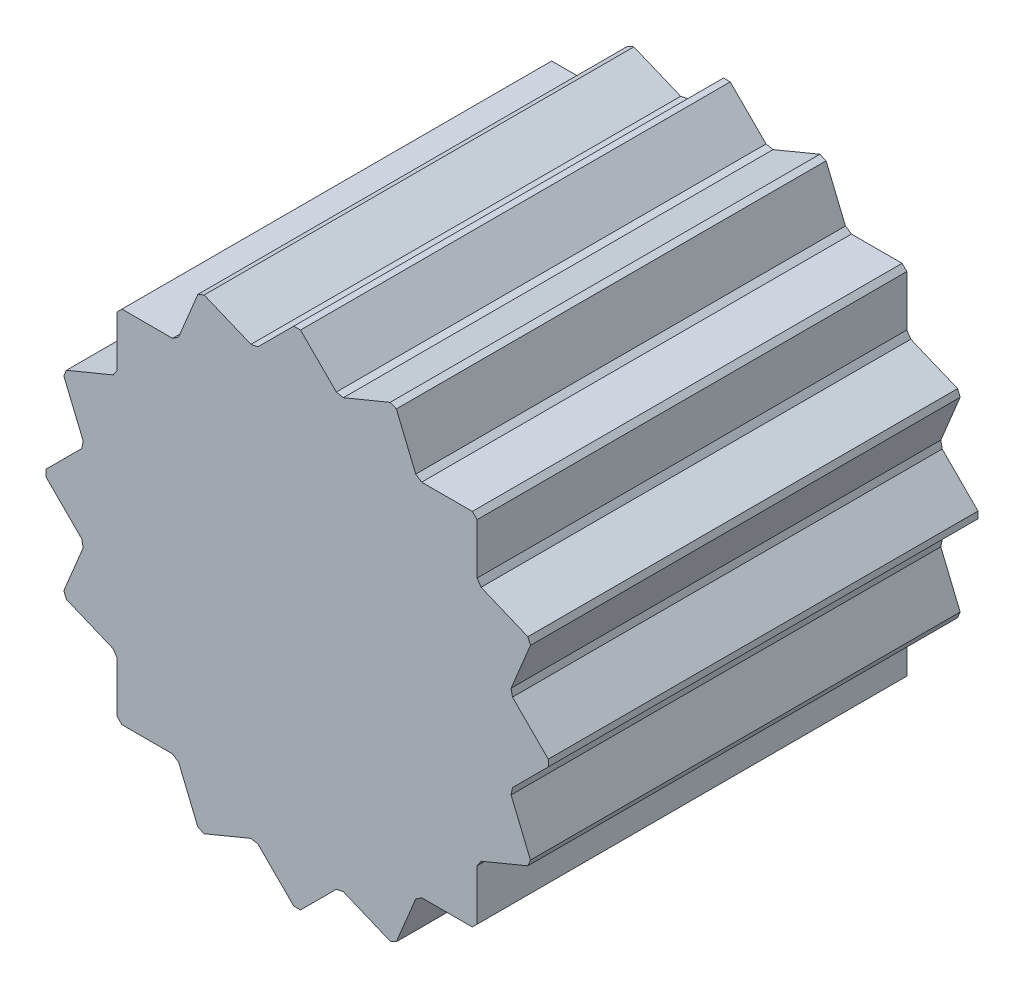
SolidWorks part; units mm, degrees
ref_plane "Front Plane" through (0, 0, 0) normal (0, 0, 1) x (1, 0, 0)
ref_plane "Top Plane" through (0, 0, 0) normal (0, 1, 0) x (1, 0, 0)
ref_plane "Right Plane" through (0, 0, 0) normal (1, 0, 0) x (0, 0, -1)
sketch "Sketch2" plane through (0, 0, 0) normal (0, 0, 1) x (1, 0, 0)
  circle A0 centre (0, 0) radius 15.2789
  dimension "D1" = 30.5577
extrude "Boss-Extrude1" add sketch "Sketch2" along normal blind 30
sketch "Sketch3" plane through (0, 0, 0) normal (0, 0, -1) x (-1, 0, 0)
  line L0 (-2.7352, 15.0321) -> (-0.2352, 17.5321)
  line L1 (-0.2352, 17.5321) -> (0.2352, 17.5321)
  line L2 (0.2352, 17.5321) -> (2.7352, 15.0321)
  line L3 (-2.7352, 15.0321) -> (2.7352, 15.0321) construction
  arc A0 (2.7352, 15.0321) -> (-2.7352, 15.0321) centre (0, 0) ccw
  circle A1 centre (0, 0) radius 15.2789 construction
  point P6 (0, 15.2789)
  point P9 (0, 17.5321)
  dimension "D1" = 45
  dimension "D2" = 2.5
  dimension "D3" = 5.5
extrude "Boss-Extrude2" add sketch "Sketch3" against normal up to surface (30 mm away) up to face at (15.2789, 0, 30)
pattern_circular "CirPattern1" count 16 over 360 about axis through (0, 0, 0) along (0, 0, 1) of "Boss-Extrude2"
equation "\"ht\"= 2.5mm"
equation "\"hb\"= 4.5mm"
equation "\"tooth_angle\"= 45deg"
equation "\"pitch\"= 6mm"
equation "\"bt\"= 5.5mm"
equation "\"num_teeth\"= 16"
equation "\"circumference\"= \"pitch\" * \"num_teeth\""
equation "\"diameter\"= \"circumference\" / pi"
equation "\"D1@Sketch2\"= \"diameter\""
equation "\"width\"= 30mm"
equation "\"D1@Sketch3\"= \"tooth_angle\""
equation "\"D2@Sketch3\"= \"ht\""
equation "\"D3@Sketch3\"=\"bt\""
equation "\"D1@CirPattern1\"= \"num_teeth\""
equation "\"D1@Boss-Extrude1\"=\"width\""
